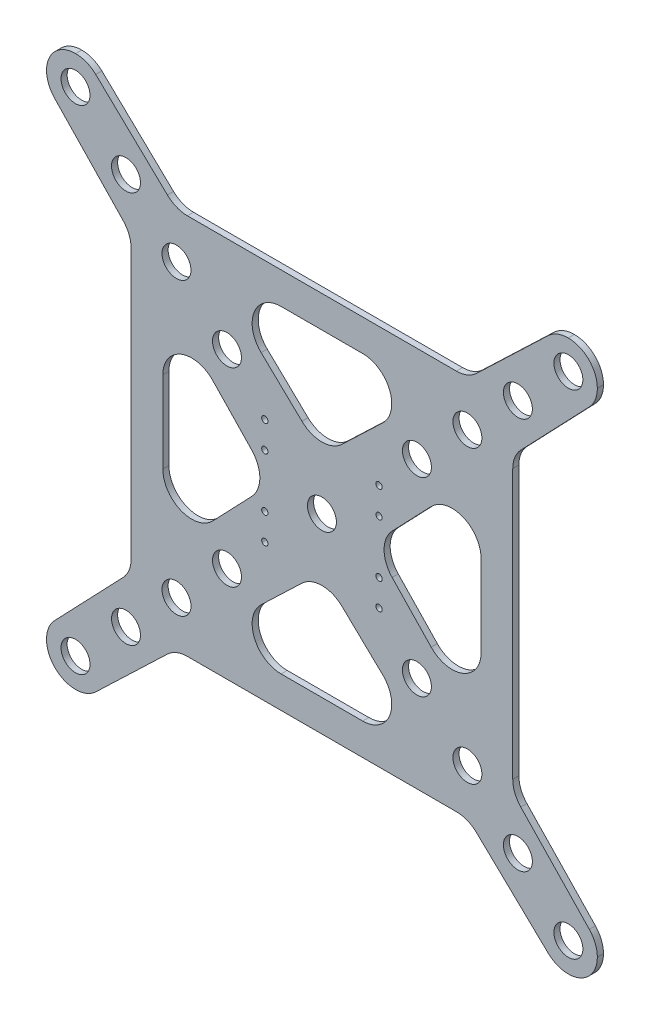
SolidWorks part; units mm, degrees
material "6061 Alloy"
ref_plane "Front Plane" through (0, 0, 0) normal (0, 0, 1) x (1, 0, 0)
ref_plane "Top Plane" through (0, 0, 0) normal (0, 1, 0) x (1, 0, 0)
ref_plane "Right Plane" through (0, 0, 0) normal (1, 0, 0) x (0, 0, -1)
sketch "Sketch1" plane through (0, 0, 0) normal (0, 0, 1) x (1, 0, 0)
  line L0 (-135, 135) -> (0, 0) construction
  line L1 (-135, 135) -> (135, 135)
  line L2 (-135, 135) -> (-135, -135)
  line L3 (-135, -135) -> (135, -135)
  line L4 (135, 135) -> (135, -135)
  line L5 (0, -135) -> (0, 135) construction
  line L6 (-135, 0) -> (135, 0) construction
  circle A0 centre (0, 0) radius 7.1
  circle A1 centre (-120.8, 120.8) radius 7.1
  circle A2 centre (0, 0) radius 15 construction
  circle A3 centre (-120.8, 120.8) radius 15 construction
  circle A4 centre (-120.8, -120.8) radius 15 construction
  circle A5 centre (-120.8, -120.8) radius 7.1
  circle A6 centre (120.8, -120.8) radius 7.1
  circle A7 centre (120.8, -120.8) radius 15 construction
  circle A8 centre (120.8, 120.8) radius 15 construction
  circle A9 centre (120.8, 120.8) radius 7.1
  circle A10 centre (-96.0513, 96.0513) radius 7.1
  circle A11 centre (-71.3025, 71.3025) radius 7.1
  circle A12 centre (-46.5538, 46.5538) radius 7.1
  circle A13 centre (46.5538, 46.5538) radius 7.1
  circle A14 centre (71.3025, 71.3025) radius 7.1
  circle A15 centre (96.0513, 96.0513) radius 7.1
  circle A16 centre (96.0513, -96.0513) radius 7.1
  circle A17 centre (71.3025, -71.3025) radius 7.1
  circle A18 centre (46.5538, -46.5538) radius 7.1
  circle A19 centre (-46.5538, -46.5538) radius 7.1
  circle A20 centre (-71.3025, -71.3025) radius 7.1
  circle A21 centre (-96.0513, -96.0513) radius 7.1
  point P0 (0, 0)
  point P23 (0, 0)
  dimension "D1" = 14.2
  dimension "D2" = 14.2
  dimension "D3" = 30
  dimension "D4" = 30
  dimension "D7" = 270
  dimension "D8" = 270
  dimension "D5" = 14.2
  dimension "D6" = 14.2
  dimension "D10" = 35
  dimension "D9" = 4
extrude "Boss-Extrude1" add sketch "Sketch1" along normal blind 3
sketch "Sketch2" plane through (0, 0, 0) normal (0, 0, 1) x (1, 0, 0)
  line L0 (135, 0) -> (-135, 0) construction
  line L1 (-23, -17.5) -> (-33, -17.5) construction
  line L2 (-23, -17.5) -> (-23, 17.5) construction
  line L3 (-23, 17.5) -> (-33, 17.5) construction
  line L4 (-33, -17.5) -> (-33, 17.5) construction
  line L5 (-28, 17.5) -> (-28, -17.5) construction
  line L6 (-23, 0) -> (-33, 0) construction
  line L7 (-135, 135) -> (-135, -135) construction
  line L8 (0, -135) -> (0, 135) construction
  line L9 (135, 135) -> (-135, 135) construction
  circle A0 centre (-28, 13) radius 1.55
  circle A1 centre (-28, -13) radius 1.55
  circle A2 centre (-28, 26) radius 1.55
  circle A3 centre (-28, -26) radius 1.55
  circle A4 centre (28, -26) radius 1.55
  circle A5 centre (28, 26) radius 1.55
  point P0 (-28, 0)
  point P15 (0, 0)
  point P20 (0, 0)
  dimension "D3" = 3.1
  dimension "D7" = 3.1
  dimension "D1" = 35
  dimension "D2" = 10
  dimension "D4" = 13
  dimension "D5" = 28
  dimension "D6" = 13
  dimension "D8" = 28
extrude "Cut-Extrude1" cut sketch "Sketch2" along normal through all both and the other way through all
mirror "Mirror1" about plane through (0, 0, 0) normal (1, 0, 0) of "Cut-Extrude1"
sketch "Sketch4" plane through (0, 0, 0) normal (0, 0, 1) x (1, 0, 0)
  line L0 (-135, 115) -> (-93.5266, 71.6415)
  line L1 (-135, 135) -> (-135, -135) construction
  line L2 (-25, 0) -> (-135, 0) construction
  line L3 (-135, -115) -> (-135, 115)
  line L5 (-135, 135) -> (0, 0) construction
  line L6 (0, 0) -> (135, 0) construction
  line L7 (135, -135) -> (135, 135) construction
  line L9 (0, 0) -> (0, 135) construction
  line L10 (135, 135) -> (-135, 135) construction
  line L12 (115, 135) -> (-115, 135)
  line L14 (-115, 135) -> (-71.6415, 93.5266)
  line L15 (115, 135) -> (71.6415, 93.5266)
  line L17 (135, -115) -> (135, 115)
  line L19 (135, 115) -> (93.5266, 71.6415)
  line L20 (135, -115) -> (93.5266, -71.6415)
  line L22 (115, -135) -> (71.6415, -93.5266)
  line L23 (-115, -135) -> (-71.6415, -93.5266)
  line L24 (-93.5266, 71.6415) -> (-93.5266, -71.6415)
  line L25 (115, -135) -> (-115, -135)
  line L26 (-135, -115) -> (-93.5266, -71.6415)
  line L28 (-78, 55.4091) -> (-78, -55.4091)
  line L29 (-93.5266, 71.6415) -> (-78, 55.4091) construction
  line L30 (-78, 55.4091) -> (-25, 0)
  line L31 (-93.5266, -71.6415) -> (-78, -55.4091) construction
  line L32 (-78, -55.4091) -> (-25, 0)
  line L33 (55.4091, 78) -> (-55.4091, 78)
  line L34 (71.6415, 93.5266) -> (-71.6415, 93.5266)
  line L35 (78, -55.4091) -> (78, 55.4091)
  line L36 (93.5266, -71.6415) -> (93.5266, 71.6415)
  line L37 (-55.4091, -78) -> (55.4091, -78)
  line L38 (-71.6415, -93.5266) -> (71.6415, -93.5266)
  line L39 (-71.6415, 93.5266) -> (-55.4091, 78) construction
  line L40 (-55.4091, 78) -> (0, 25)
  line L41 (71.6415, 93.5266) -> (55.4091, 78) construction
  line L42 (55.4091, 78) -> (0, 25)
  line L43 (93.5266, 71.6415) -> (78, 55.4091) construction
  line L44 (78, 55.4091) -> (25, 0)
  line L45 (93.5266, -71.6415) -> (78, -55.4091) construction
  line L46 (78, -55.4091) -> (25, 0)
  line L47 (71.6415, -93.5266) -> (55.4091, -78) construction
  line L48 (55.4091, -78) -> (0, -25)
  line L49 (-71.6415, -93.5266) -> (-55.4091, -78) construction
  line L50 (-55.4091, -78) -> (0, -25)
  point P44 (0, 0)
  dimension "D1" = 115
  dimension "D2" = 110
  dimension "D3" = 53
  dimension "D4" = 60
  dimension "D5" = 4
extrude "Cut-Extrude2" cut sketch "Sketch4" along normal through all both and the other way through all
fillet "Fillet1" radius 14.2 32 edges at (135, 135, 1.5) (135, -135, 1.5) (-135, -135, 1.5) (-135, 135, 1.5) (135, -115, 1.5) (115, -135, 1.5) (-115, -135, 1.5) (-135, -115, 1.5) (-135, 115, 1.5) (-115, 135, 1.5) (115, 135, 1.5) (135, 115, 1.5) (-55.4091, 78, 1.5) (0, 25, 1.5) (55.4091, 78, 1.5) (-78, 55.4091, 1.5) (-78, -55.4091, 1.5) (55.4091, -78, 1.5) (0, -25, 1.5) (-55.4091, -78, 1.5) (-25, 0, 1.5) (25, 0, 1.5) (78, -55.4091, 1.5) (78, 55.4091, 1.5) (93.5266, -71.6415, 1.5) (71.6415, -93.5266, 1.5) (-71.6415, -93.5266, 1.5) (-93.5266, -71.6415, 1.5) (-71.6415, 93.5266, 1.5) (71.6415, 93.5266, 1.5) (93.5266, 71.6415, 1.5) (-93.5266, 71.6415, 1.5)
equation "\"D1@Sketch1\"=\"D2@Sketch1\""
equation "\"Tolerance\"= 0.2"
equation "\"D2@Sketch1\"=14+\"Tolerance\""
equation "\"D7@Sketch1\"=\"D8@Sketch1\""
equation "\"D6@Sketch1\"=\"D5@Sketch1\""
equation "\"D6@Sketch2\"=\"D4@Sketch2\""
equation "\"D7@Sketch2\"=\"D3@Sketch2\""
